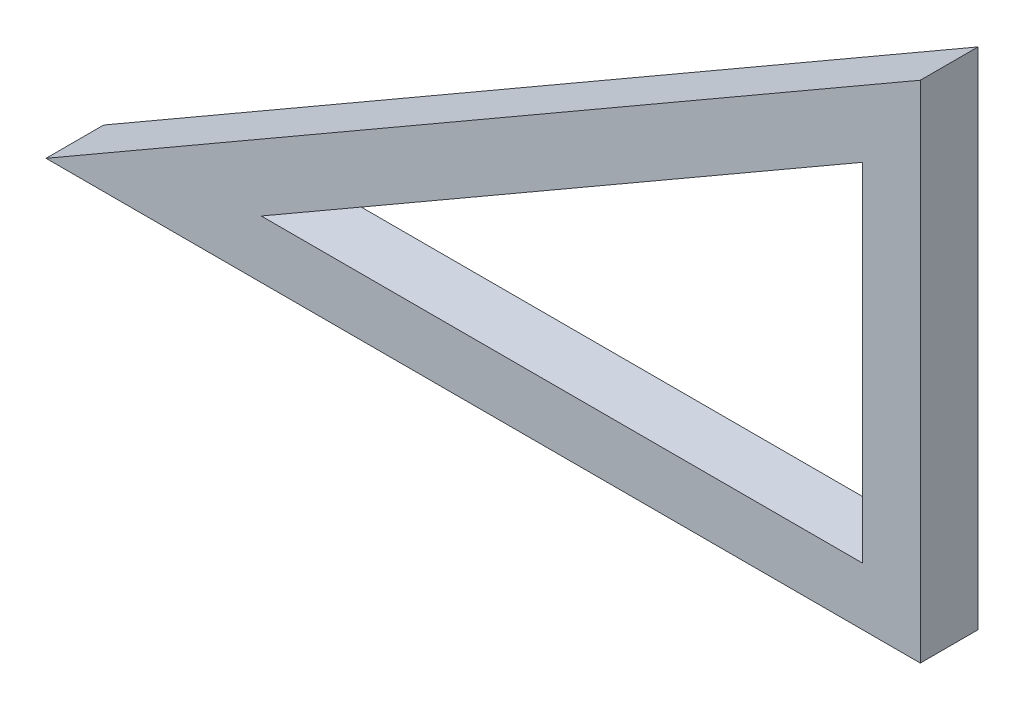
SolidWorks part; units mm, degrees
ref_plane "Front Plane" through (0, 0, 0) normal (0, 0, 1) x (1, 0, 0)
ref_plane "Top Plane" through (0, 0, 0) normal (0, 1, 0) x (1, 0, 0)
ref_plane "Right Plane" through (0, 0, 0) normal (1, 0, 0) x (0, 0, -1)
sketch "Sketch1" plane through (0, 0, 0) normal (0, 0, 1) x (1, 0, 0)
  line L0 (0, 0) -> (303.1089, 0)
  line L1 (303.1089, 0) -> (303.1089, 175)
  line L2 (303.1089, 175) -> (0, 0)
  line L3 (283.1089, 140.359) -> (74.641, 20)
  line L4 (74.641, 20) -> (283.1089, 20)
  line L5 (283.1089, 20) -> (283.1089, 140.359)
  dimension "D1" = 30
  dimension "D2" = 350
  dimension "D3" = 20
extrude "Boss-Extrude1" add sketch "Sketch1" along normal blind 20
